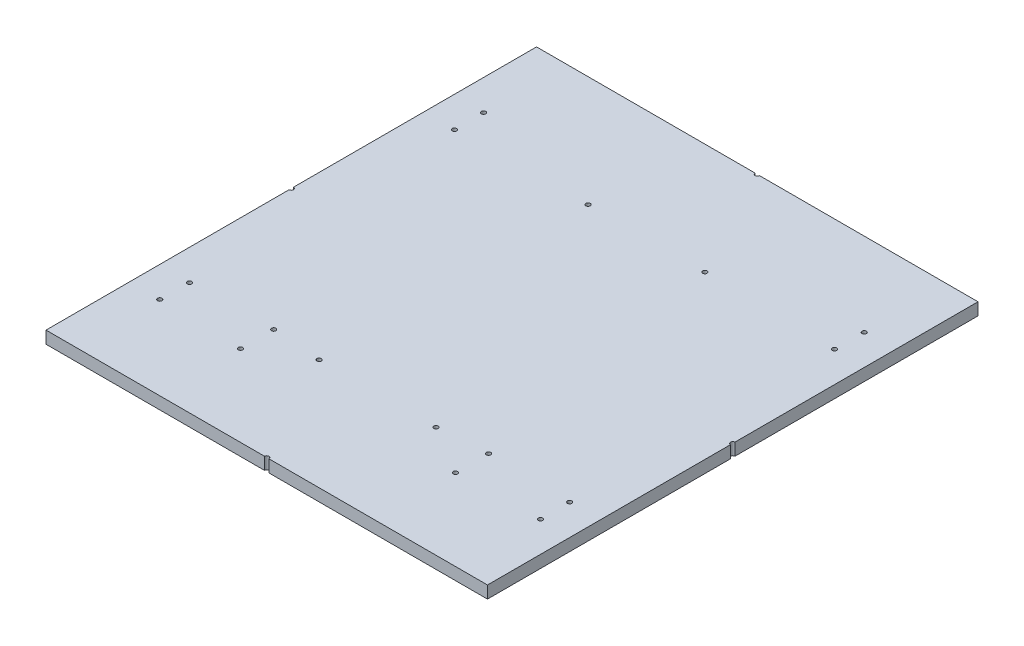
SolidWorks part; units mm, degrees
ref_plane "Front Plane" through (0, 0, 0) normal (0, 0, 1) x (1, 0, 0)
ref_plane "Top Plane" through (0, 0, 0) normal (0, 1, 0) x (1, 0, 0)
ref_plane "Right Plane" through (0, 0, 0) normal (1, 0, 0) x (0, 0, -1)
sketch "Sketch1" plane through (0, 0, 0) normal (0, 1, 0) x (1, 0, 0)
  line L1 (0, 0) -> (228.6, 0)
  line L2 (0, 0) -> (0, 254)
  line L3 (0, 254) -> (228.6, 254)
  line L4 (228.6, 0) -> (228.6, 254)
  dimension "D1" = 228.6
  dimension "D2" = 254
extrude "Boss-Extrude1" add sketch "Sketch1" along normal blind 6.35
hole_wizard "#4-40 Tapped Hole1" positions "Sketch2" profile "Sketch3" tap size "#4-40" standard "ANSI Inch" end condition through all
sketch "Sketch2" plane through (0, 6.35, 0) normal (0, 1, 0) x (1, 0, 0)
  line L0 (-228.6, 127) -> (228.6, 127) construction
  line L2 (228.6, 0) -> (228.6, 254) construction
  line L4 (114.3, -254) -> (114.3, 254) construction
  line L6 (228.6, 254) -> (0, 254) construction
  circle A0 centre (84.0588, 57.3884) radius 1.4224
  circle A1 centre (144.5617, 57.3884) radius 1.4224
  point P0 (15.7352, 43.18)
  point P3 (15.875, 58.42)
  point P7 (84.0588, 57.3884)
  point P10 (144.5617, 57.3884)
  point P89 (0, 127)
  point P92 (144.5617, 196.6116)
  point P93 (84.0588, 196.6116)
  point P94 (15.875, 195.58)
  point P95 (15.7352, 210.82)
  point P139 (114.3, 0)
  point P142 (212.8648, 43.18)
  point P143 (212.725, 58.42)
  point P144 (212.8648, 210.82)
  point P145 (212.725, 195.58)
  point P146 (228.6, 127)
  point P147 (114.3, 254)
  dimension "D2" = 2.8448
  dimension "D1" = 2.8448
sketch "Sketch3" plane through (15.7352, 6.35, -43.18) normal (1, 0, 0) x (0, 0, 1)
  line L0 (0, 0) -> (0, 6.35)
  line L1 (0, 6.35) -> (1.1303, 6.35)
  line L2 (1.1303, 6.35) -> (1.1303, 0)
  line L5 (1.1303, 0) -> (0, 0)
  line L11 (0, -6.35) -> (0, 107.95) construction
  dimension "Thru Tap Drill Dia." = 2.2606
  dimension "Thru Tap Drill Depth" = 6.35
cosmetic thread "Hole Thread1" parameters "D2"=2.8448
cosmetic thread "Hole Thread2" parameters "D2"=2.8448
cosmetic thread "Hole Thread3" parameters "D2"=2.8448
cosmetic thread "Hole Thread4" parameters "D2"=2.8448
cosmetic thread "Hole Thread5" parameters "D2"=2.8448
cosmetic thread "Hole Thread6" parameters "D2"=2.8448
cosmetic thread "Hole Thread7" parameters "D2"=2.8448
cosmetic thread "Hole Thread8" parameters "D2"=2.8448
cosmetic thread "Hole Thread9" parameters "D2"=2.8448
cosmetic thread "Hole Thread10" parameters "D2"=2.8448
cosmetic thread "Hole Thread11" parameters "D2"=2.8448
cosmetic thread "Hole Thread12" parameters "D2"=2.8448
cosmetic thread "Hole Thread13" parameters "D2"=2.8448
cosmetic thread "Hole Thread14" parameters "D2"=2.8448
cosmetic thread "Hole Thread15" parameters "D2"=2.8448
cosmetic thread "Hole Thread16" parameters "D2"=2.8448
sketch "Sketch4" plane through (0, 6.35, 0) normal (0, 1, 0) x (1, 0, 0)
  circle A0 centre (84.0588, 57.3884) radius 1.1303 construction
  circle A1 centre (144.5617, 57.3884) radius 1.1303 construction
  point P0 (58.6588, 59.1895)
  point P1 (58.6588, 42.0497)
  point P2 (169.9617, 59.1895)
  point P3 (169.9617, 42.0497)
  dimension "D3" = 25.4
  dimension "D1" = 25.4
  dimension "D2" = 25.4
  dimension "D4" = 25.4
hole_wizard "#4-40 Tapped Hole2" positions "Sketch4" profile "Sketch5" tap size "#4-40" standard "ANSI Inch" end condition through all
sketch "Sketch5" plane through (58.6588, 6.35, -59.1895) normal (1, 0, 0) x (0, 0, 1)
  line L0 (0, 0) -> (0, 6.35)
  line L1 (0, 6.35) -> (1.1303, 6.35)
  line L2 (1.1303, 6.35) -> (1.1303, 0)
  line L5 (1.1303, 0) -> (0, 0)
  line L11 (0, -6.35) -> (0, 107.95) construction
  dimension "Thru Tap Drill Dia." = 2.2606
  dimension "Thru Tap Drill Depth" = 6.35
